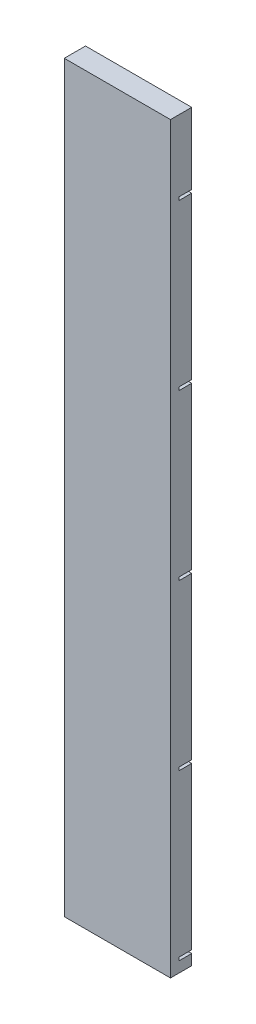
SolidWorks part; units mm, degrees
ref_plane "Front Plane" through (0, 0, 0) normal (0, 0, 1) x (1, 0, 0)
ref_plane "Top Plane" through (0, 0, 0) normal (0, 1, 0) x (1, 0, 0)
ref_plane "Right Plane" through (0, 0, 0) normal (1, 0, 0) x (0, 0, -1)
sketch "Sketch1" plane through (0, 0, 0) normal (1, 0, 0) x (0, 0, -1)
  line L0 (10, 6.5) -> (10, 82.5)
  line L1 (0, 0) -> (10, 0)
  line L2 (0, 0) -> (0, 350)
  line L3 (0, 350) -> (10, 350)
  line L4 (10, 0) -> (10, 5)
  line L5 (10, 5) -> (4, 5)
  line L7 (10, 6.5) -> (4, 6.5)
  line L8 (4, 5) -> (4, 6.5)
  line L9 (10, 82.5) -> (4, 82.5)
  line L10 (10, 84) -> (4, 84)
  line L11 (4, 82.5) -> (4, 84)
  line L12 (10, 160) -> (4, 160)
  line L13 (10, 161.5) -> (4, 161.5)
  line L14 (4, 160) -> (4, 161.5)
  line L15 (10, 237.5) -> (4, 237.5)
  line L16 (10, 239) -> (4, 239)
  line L17 (4, 237.5) -> (4, 239)
  line L18 (10, 315) -> (4, 315)
  line L19 (10, 316.5) -> (4, 316.5)
  line L20 (4, 315) -> (4, 316.5)
  line L21 (10, 316.5) -> (10, 350)
  line L22 (10, 239) -> (10, 315)
  line L23 (10, 161.5) -> (10, 237.5)
  line L24 (10, 84) -> (10, 160)
  dimension "D1" = 10
  dimension "D2" = 350
  dimension "D3" = 1.5
  dimension "D4" = 5
  dimension "D5" = 6
  dimension "D7" = 77.5
  dimension "D6" = 5
extrude "Boss-Extrude1" add sketch "Sketch1" along normal blind 50
